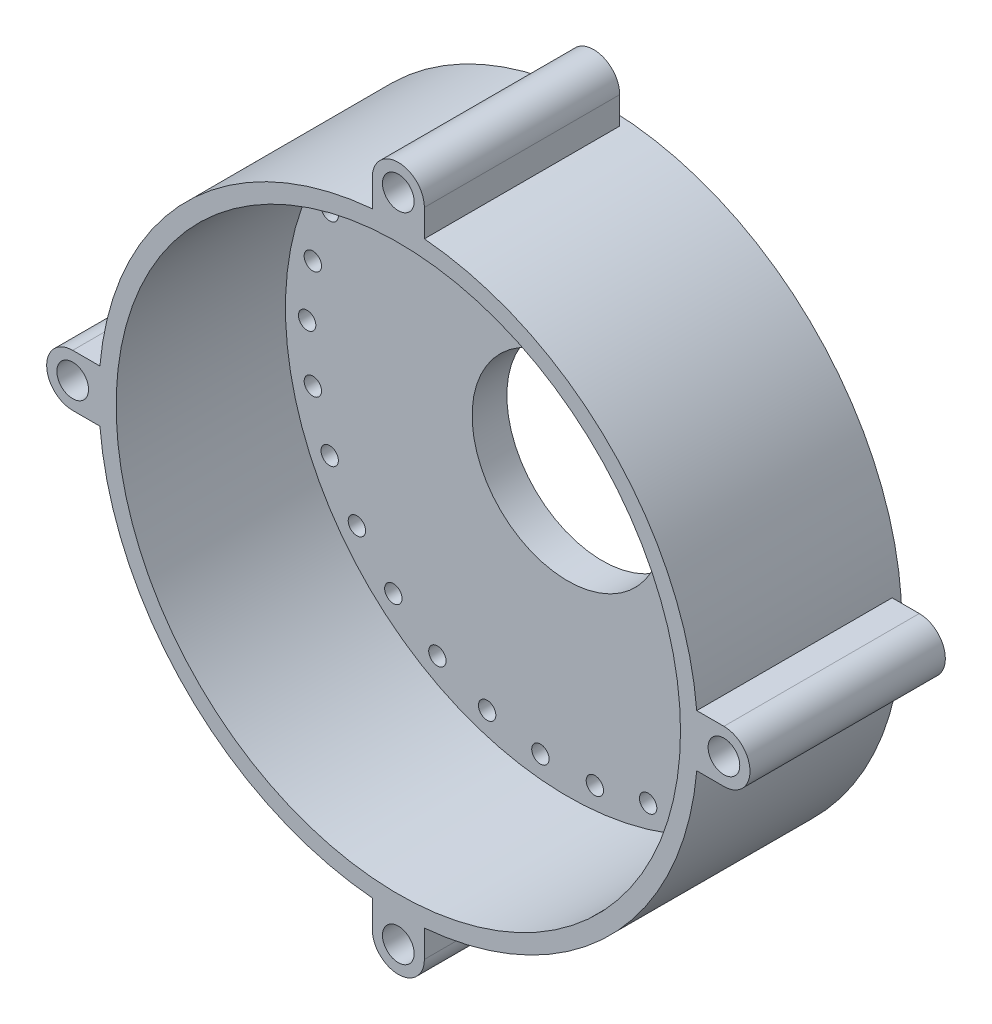
SolidWorks part; units mm, degrees
ref_plane "Front Plane" through (0, 0, 0) normal (0, 0, 1) x (1, 0, 0)
ref_plane "Top Plane" through (0, 0, 0) normal (0, 1, 0) x (1, 0, 0)
ref_plane "Right Plane" through (0, 0, 0) normal (1, 0, 0) x (0, 0, -1)
sketch "Sketch1" plane through (0, 0, 0) normal (0, 0, 1) x (1, 0, 0)
  circle A0 centre (0, 0) radius 54.7687
  dimension "D1" = 109.5375
extrude "Boss-Extrude1" add sketch "Sketch1" along normal blind 37.3062
sketch "Sketch2" plane through (0, 0, 37.3062) normal (0, 0, 1) x (1, 0, 0)
  line L0 (0, 0) -> (-96.755, 0) construction
  circle A0 centre (0, 0) radius 51.5938
  circle A1 centre (0, 0) radius 54.7687 construction
  dimension "D1" = 3.175
extrude "Cut-Extrude1" cut sketch "Sketch2" against normal offset from surface (30.9563 mm away) 6.35 up to face at (54.7687, 0, 0)
sketch "Sketch3" plane through (0, 0, 6.35) normal (0, 0, 1) x (1, 0, 0)
  line L0 (1.0369, 0) -> (-103.1353, 0) construction
  circle A0 centre (0, 0) radius 47.625 construction
  circle A1 centre (-47.625, 0) radius 1.5875
  circle A2 centre (-46.5843, 9.9018) radius 1.5875
  circle A3 centre (-43.5076, 19.3708) radius 1.5875
  circle A4 centre (-38.5294, 27.9933) radius 1.5875
  circle A5 centre (-31.8673, 35.3923) radius 1.5875
  circle A6 centre (-23.8125, 41.2445) radius 1.5875
  circle A7 centre (-14.7169, 45.2941) radius 1.5875
  circle A8 centre (-4.9782, 47.3641) radius 1.5875
  circle A9 centre (4.9782, 47.3641) radius 1.5875
  circle A10 centre (14.7169, 45.2941) radius 1.5875
  circle A11 centre (23.8125, 41.2445) radius 1.5875
  circle A12 centre (31.8673, 35.3923) radius 1.5875
  circle A13 centre (38.5294, 27.9933) radius 1.5875
  circle A14 centre (43.5076, 19.3708) radius 1.5875
  circle A15 centre (46.5843, 9.9018) radius 1.5875
  circle A16 centre (0, 0) radius 51.5938 construction
  circle A17 centre (47.625, 0) radius 1.5875
  circle A18 centre (46.5843, -9.9018) radius 1.5875
  circle A19 centre (43.5076, -19.3708) radius 1.5875
  circle A20 centre (38.5294, -27.9933) radius 1.5875
  circle A21 centre (31.8673, -35.3923) radius 1.5875
  circle A22 centre (23.8125, -41.2445) radius 1.5875
  circle A23 centre (14.7169, -45.2941) radius 1.5875
  circle A24 centre (4.9782, -47.3641) radius 1.5875
  circle A25 centre (-4.9782, -47.3641) radius 1.5875
  circle A26 centre (-14.7169, -45.2941) radius 1.5875
  circle A27 centre (-23.8125, -41.2445) radius 1.5875
  circle A28 centre (-31.8673, -35.3923) radius 1.5875
  circle A29 centre (-38.5294, -27.9933) radius 1.5875
  circle A30 centre (-43.5076, -19.3708) radius 1.5875
  circle A31 centre (-46.5843, -9.9018) radius 1.5875
  point P37 (0, 0)
  dimension "D1" = 95.25
  dimension "D2" = 3.175
  dimension "D3" = 30
extrude "Cut-Extrude2" cut sketch "Sketch3" against normal blind 3.175
sketch "Sketch4" plane through (0, 0, 6.35) normal (0, 0, 1) x (1, 0, 0)
  circle A0 centre (0, 0) radius 17.4625
  dimension "D1" = 34.925
extrude "Cut-Extrude3" cut sketch "Sketch4" against normal through all
sketch "Sketch7" plane through (0, 0, 37.3062) normal (0, 0, 1) x (1, 0, 0)
  line L0 (-59.5312, 4.7625) -> (-54.5613, 4.7625)
  line L1 (-59.5312, -4.7625) -> (-54.5613, -4.7625)
  line L2 (0, 0) -> (-59.5312, 0) construction
  line L3 (-4.7625, 59.5312) -> (-4.7625, 54.5613)
  line L4 (4.7625, 59.5312) -> (4.7625, 54.5613)
  line L5 (59.5312, 4.7625) -> (54.5613, 4.7625)
  line L6 (59.5312, -4.7625) -> (54.5613, -4.7625)
  line L7 (4.7625, -59.5312) -> (4.7625, -54.5613)
  line L8 (-4.7625, -59.5312) -> (-4.7625, -54.5613)
  arc A0 (-59.5312, 4.7625) -> (-59.5312, -4.7625) centre (-59.5312, 0) ccw
  circle A1 centre (0, 0) radius 54.7687 construction
  arc A2 (4.7625, 59.5312) -> (-4.7625, 59.5312) centre (0, 59.5312) ccw
  arc A3 (59.5312, -4.7625) -> (59.5312, 4.7625) centre (59.5312, 0) ccw
  arc A4 (-4.7625, -59.5312) -> (4.7625, -59.5312) centre (0, -59.5312) ccw
  circle A6 centre (0, 0) radius 54.7687
  point P27 (0, 0)
  dimension "D1" = 9.525
  dimension "D2" = 4
extrude "Boss-Extrude2" add sketch "Sketch7" against normal blind 35.7188
sketch "Sketch8" plane through (0, 0, 37.3062) normal (0, 0, 1) x (1, 0, 0)
  point P0 (-59.5312, 0)
  point P1 (0, 59.5312)
  point P3 (59.5312, 0)
  point P5 (0, -59.5312)
sketch "Sketch9" plane through (0, 0, 37.3062) normal (0, 0, 1) x (1, 0, 0)
  point P0 (-59.5312, 0)
  point P3 (0, 59.5312)
  point P6 (59.5312, 0)
  point P9 (0, -59.5312)
hole_wizard "#1 (0.228) Diameter Hole1" positions "Sketch9" profile "Sketch10" hole size "#1" standard "ANSI Inch" end condition through all
sketch "Sketch10" plane through (-59.5312, 0, 37.3062) normal (1, 0, 0) x (0, -1, 0)
  line L0 (0, 0) -> (0, 37.3062)
  line L1 (0, 37.3062) -> (2.8956, 37.3062)
  line L2 (2.8956, 37.3062) -> (2.8956, 0)
  line L5 (2.8956, 0) -> (0, 0)
  line L11 (0, -6.35) -> (0, 107.95) construction
  dimension "Thru Hole Dia." = 5.7912
  dimension "Thru Hole Depth" = 37.3062
